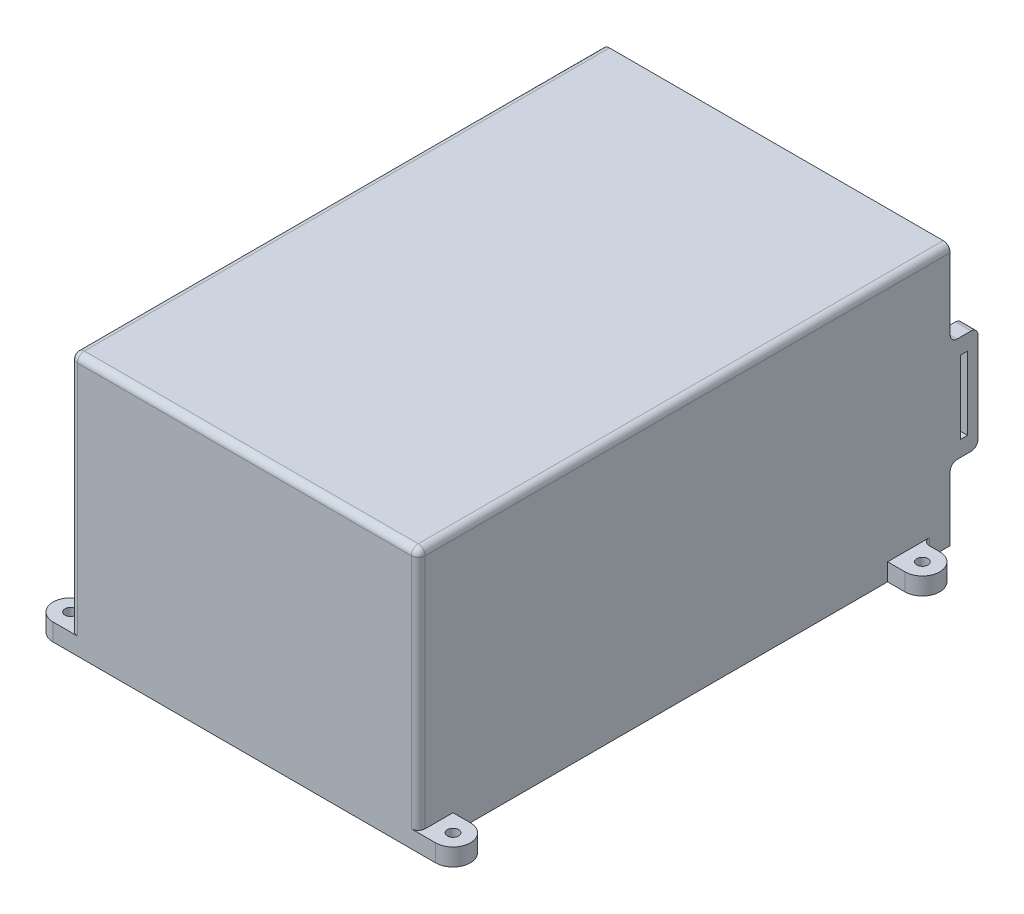
SolidWorks part; units mm, degrees
ref_plane "Front Plane" through (0, 0, 0) normal (0, 0, 1) x (1, 0, 0)
ref_plane "Top Plane" through (0, 0, 0) normal (0, 1, 0) x (1, 0, 0)
ref_plane "Right Plane" through (0, 0, 0) normal (1, 0, 0) x (0, 0, -1)
sketch "Sketch2" plane through (0, 0, 0) normal (0, 1, 0) x (1, 0, 0)
  line L1 (-50, -72.5) -> (50, -72.5)
  line L2 (-50, -72.5) -> (-50, 72.5)
  line L3 (-50, 72.5) -> (50, 72.5)
  line L4 (50, -72.5) -> (50, 72.5)
  line L5 (-50, -72.5) -> (50, 72.5) construction
  line L6 (-50, 72.5) -> (50, -72.5) construction
  point P0 (0, 0)
  dimension "D1" = 145
  dimension "D2" = 100
extrude "Boss-Extrude1" add sketch "Sketch2" along normal blind 75
sketch "Sketch3" plane through (0, 0, 0) normal (0, -1, 0) x (1, 0, 0)
  line L1 (45.5, 67.5) -> (-45.5, 67.5)
  line L2 (45.5, 67.5) -> (45.5, -72.5)
  line L3 (45.5, -72.5) -> (-45.5, -72.5)
  line L4 (-45.5, 67.5) -> (-45.5, -72.5)
  line L5 (50, -72.5) -> (-50, -72.5) construction
  line L6 (-50, 72.5) -> (50, 72.5) construction
  point P8 (0, 67.5)
  point P11 (0, 72.5)
  dimension "D1" = 91
  dimension "D2" = 140
extrude "Cut-Extrude1" cut sketch "Sketch3" against normal blind 71
sketch "Sketch4" plane through (0, 0, 0) normal (0, -1, 0) x (1, 0, 0)
  line L19 (-50, 72.5) -> (-55, 72.5)
  line L20 (-50, 72.5) -> (-50, 62.5)
  line L21 (-50, 62.5) -> (-55, 62.5)
  line L22 (-55, 72.5) -> (-55, 62.5) construction
  line L23 (50, 72.5) -> (55, 72.5)
  line L24 (50, 72.5) -> (50, 62.5)
  line L25 (50, 62.5) -> (55, 62.5)
  line L26 (55, 72.5) -> (55, 62.5) construction
  line L27 (-50, -72.5) -> (-55, -72.5)
  line L28 (-50, -72.5) -> (-50, -62.5)
  line L29 (-50, -62.5) -> (-55, -62.5)
  line L30 (-55, -72.5) -> (-55, -62.5) construction
  line L31 (50, -72.5) -> (55, -72.5)
  line L32 (50, -72.5) -> (50, -62.5)
  line L33 (50, -62.5) -> (55, -62.5)
  line L34 (55, -72.5) -> (55, -62.5) construction
  arc A0 (-55, 72.5) -> (-55, 62.5) centre (-55, 67.5) ccw
  arc A1 (55, 72.5) -> (55, 62.5) centre (55, 67.5) cw
  arc A2 (55, -62.5) -> (55, -72.5) centre (55, -67.5) cw
  arc A3 (-55, -62.5) -> (-55, -72.5) centre (-55, -67.5) ccw
  dimension "D1" = 10
  dimension "D2" = 5
extrude "Boss-Extrude2" add sketch "Sketch4" against normal blind 5
hole_wizard "M3 Clearance Hole2" positions "Sketch8" profile "Sketch9" hole size "M3" standard "ANSI Metric"
sketch "Sketch8" plane through (0, 5, 0) normal (0, 1, 0) x (1, 0, 0)
  point P20 (-55, 67.5)
  point P23 (55, 67.5)
  point P26 (55, -67.5)
  point P29 (-55, -67.5)
sketch "Sketch9" plane through (-55, 5, -67.5) normal (1, 0, 0) x (0, 0, 1)
  line L0 (0, 0) -> (0, 12.9614)
  line L1 (0, 12.9614) -> (1.6, 12)
  line L2 (1.6, 12) -> (1.6, 0)
  line L5 (1.6, 0) -> (0, 0)
  line L10 (0, 12.9614) -> (-1.6, 12) construction
  line L11 (0, -6.35) -> (0, 107.95) construction
  dimension "Hole Dia." = 3.2
  dimension "Hole Depth" = 12
  dimension "Drill Angle" = 118
ref_plane "Plane2" through (0, 0, 12.5) normal (0, 0, -1) x (-1, 0, 0)
sketch "Sketch11" plane through (0, 0, 12.5) normal (0, 0, -1) x (-1, 0, 0)
  line L0 (50, 75) -> (50, 5) construction
  line L1 (50, 50.5) -> (58, 50.5)
  line L2 (50, 50.5) -> (50, 20.5)
  line L3 (50, 20.5) -> (58, 20.5)
  line L4 (58, 50.5) -> (58, 20.5)
  line L5 (45.5, 71) -> (45.5, 0) construction
  line L9 (53, 25) -> (55, 25)
  line L10 (53, 25) -> (53, 46)
  line L11 (53, 46) -> (55, 46)
  line L12 (55, 25) -> (55, 46)
  line L13 (53, 25) -> (55, 46) construction
  line L14 (53, 46) -> (55, 25) construction
  point P6 (50, 35.5)
  point P9 (45.5, 35.5)
  point P14 (54, 35.5)
  point P20 (58, 35.5)
  point P21 (54, 50.5)
  dimension "D1" = 21
  dimension "D2" = 2
  dimension "D3" = 8
  dimension "D4" = 30
extrude "Boss-Extrude4" add sketch "Sketch11" along normal mid plane 8
sketch "Sketch13" plane through (0, 0, 67.5) normal (0, 0, -1) x (-1, 0, 0)
  line L4 (-45.5, 0) -> (45.5, 0)
  line L5 (45.5, 0) -> (45.5, 71)
  line L6 (45.5, 71) -> (-45.5, 71)
  line L7 (-45.5, 71) -> (-45.5, 0)
  line L8 (-45.5, 0) -> (45.5, 0)
  line L9 (45.5, 0) -> (45.5, 71)
  line L10 (45.5, 71) -> (-45.5, 71)
  line L11 (-45.5, 71) -> (-45.5, 0)
  dimension "D1" = 0
extrude "Boss-Extrude6" add sketch "Sketch13" along normal blind 8
sketch "Sketch15" plane through (0, 0, -72.5) normal (0, 0, -1) x (-1, 0, 0)
  line L0 (-50, 5) -> (-50, 0)
  line L1 (50, 5) -> (50, 0)
  line L12 (-55, 0) -> (-45.5, 0)
  line L13 (-45.5, 0) -> (-45.5, 71)
  line L14 (-45.5, 71) -> (45.5, 71)
  line L15 (45.5, 71) -> (45.5, 0)
  line L16 (45.5, 0) -> (55, 0)
  line L17 (55, 0) -> (55, 5)
  line L18 (55, 5) -> (50, 5)
  line L19 (50, 5) -> (50, 75)
  line L20 (50, 75) -> (-50, 75)
  line L21 (-50, 75) -> (-50, 5)
  line L22 (-50, 5) -> (-55, 5)
  line L23 (-55, 5) -> (-55, 0)
  line L24 (-50, 0) -> (-45.5, 0)
  line L25 (-45.5, 0) -> (-45.5, 71)
  line L26 (-45.5, 71) -> (45.5, 71)
  line L27 (45.5, 71) -> (45.5, 0)
  line L28 (45.5, 0) -> (50, 0)
  line L31 (50, 5) -> (50, 75)
  line L32 (50, 75) -> (-50, 75)
  line L33 (-50, 75) -> (-50, 5)
  dimension "D1" = 0
extrude "Boss-Extrude7" add sketch "Sketch15" along normal blind 8
sketch "Sketch12" plane through (50, 0, 0) normal (1, 0, 0) x (0, 0, -1)
  line L1 (80.5, 50.5) -> (88.5, 50.5)
  line L2 (80.5, 50.5) -> (80.5, 20.5)
  line L3 (80.5, 20.5) -> (88.5, 20.5)
  line L4 (88.5, 50.5) -> (88.5, 20.5)
  line L5 (80.5, 75) -> (80.5, 0) construction
  line L6 (83.5, 25) -> (85.5, 25)
  line L7 (83.5, 25) -> (83.5, 46)
  line L8 (83.5, 46) -> (85.5, 46)
  line L9 (85.5, 25) -> (85.5, 46)
  line L10 (83.5, 25) -> (85.5, 46) construction
  line L11 (83.5, 46) -> (85.5, 25) construction
  line L12 (80.5, 71) -> (80.5, 0) construction
  line L13 (80.5, 0) -> (72.5, 0) construction
  point P6 (84.5, 35.5)
  point P11 (80.5, 35.5)
  point P12 (84.5, 50.5)
  point P15 (80.5, 35.5)
  dimension "D1" = 2
  dimension "D2" = 8
  dimension "D3" = 30
  dimension "D4" = 21
  dimension "D5" = 20.5
extrude "Boss-Extrude5" add sketch "Sketch12" against normal up to surface (4.5 mm away) up to face at (45.5, 35.5, -10.5)
fillet "Fillet1" radius 2 15 edges at (-50, 50.5, 12.5) (-50, 20.5, 12.5) (-58, 20.5, 12.5) (-58, 50.5, 12.5) (-50, 75, -4) (-50, 2.5, -72.5) (50, 2.5, -72.5) (0, 75, 72.5) (47.75, 20.5, -88.5) (47.75, 50.5, -88.5) (47.75, 50.5, -80.5) (47.75, 20.5, -80.5) (50, 75, -4) (50, 40, 72.5) (-50, 40, 72.5)
